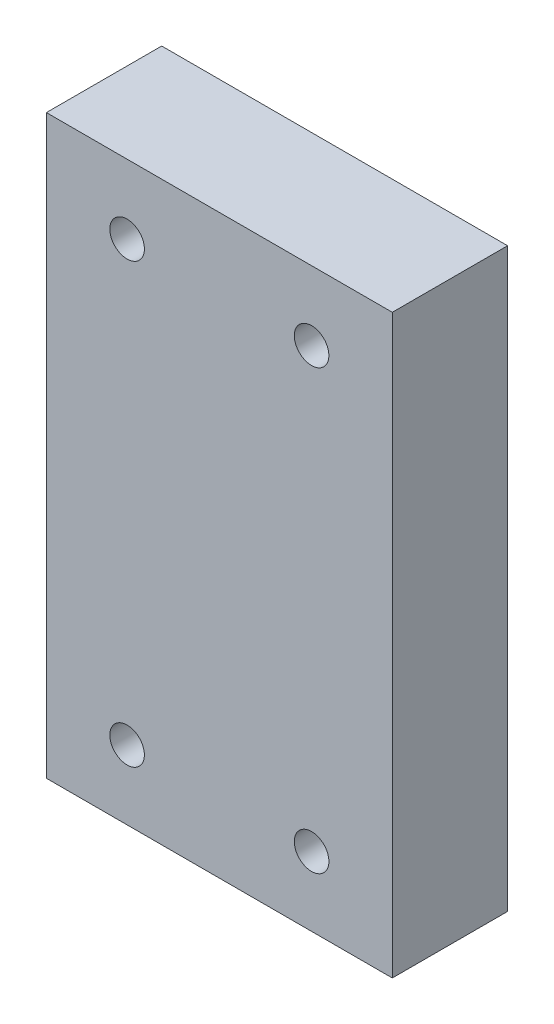
SolidWorks part; units mm, degrees
ref_plane "Front Plane" through (0, 0, 0) normal (0, 0, 1) x (1, 0, 0)
ref_plane "Top Plane" through (0, 0, 0) normal (0, 1, 0) x (1, 0, 0)
ref_plane "Right Plane" through (0, 0, 0) normal (1, 0, 0) x (0, 0, -1)
sketch "Sketch1" plane through (0, 0, 0) normal (0, 0, 1) x (1, 0, 0)
  line L0 (0, 25) -> (0, 0) construction
  line L1 (15, -25) -> (-15, -25)
  line L2 (15, -25) -> (15, 25)
  line L3 (15, 25) -> (-15, 25)
  line L4 (-15, -25) -> (-15, 25)
  line L5 (15, -25) -> (-15, 25) construction
  line L6 (15, 25) -> (-15, -25) construction
  circle A0 centre (-8, 19) radius 1.5
  circle A1 centre (8, 19) radius 1.5
  circle A2 centre (8, -19) radius 1.5
  circle A3 centre (-8, -19) radius 1.5
  point P0 (0, 0)
  dimension "D3" = 16
  dimension "D4" = 16
  dimension "D5" = 38
  dimension "D6" = 38
  dimension "D8" = 3
  dimension "D1" = 30
  dimension "D2" = 50
  dimension "D7" = 19
extrude "Boss-Extrude1" add sketch "Sketch1" along normal blind 10
sketch "Sketch3" plane through (-15, 0, 0) normal (-1, 0, 0) x (0, 0, 1)
  line L0 (5, 25) -> (5, 0) construction
  line L1 (10, 25) -> (0, 25) construction
  line L2 (5, 0) -> (0, 0) construction
  circle A0 centre (5, 12.5) radius 2
  circle A1 centre (5, -12.5) radius 2
  dimension "D1" = 25
  dimension "D2" = 4
extrude "Cut-Extrude1" cut sketch "Sketch3" against normal blind 10
